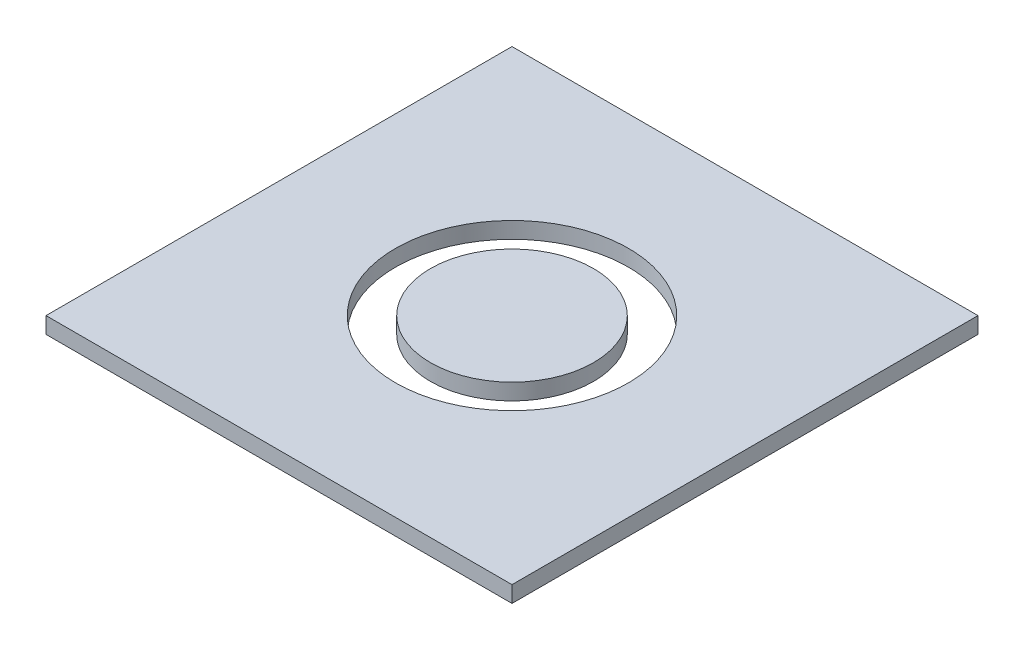
SolidWorks part; units mm, degrees
ref_plane "Front Plane" through (0, 0, 0) normal (0, 0, 1) x (1, 0, 0)
ref_plane "Top Plane" through (0, 0, 0) normal (0, 1, 0) x (1, 0, 0)
ref_plane "Right Plane" through (0, 0, 0) normal (1, 0, 0) x (0, 0, -1)
sketch "Sketch3" plane through (0, 0, 0) normal (0, 1, 0) x (1, 0, 0)
  line L1 (-10, 10) -> (10, 10)
  line L2 (-10, 10) -> (-10, -10)
  line L3 (-10, -10) -> (10, -10)
  line L4 (10, 10) -> (10, -10)
  line L5 (-10, 10) -> (10, -10) construction
  line L6 (-10, -10) -> (10, 10) construction
  point P0 (0, 0)
  dimension "D1" = 20
  dimension "D2" = 20
extrude "Boss-Extrude3" add sketch "Sketch3" along normal blind 0.7 contours L2 L3 L4 L1
sketch "Sketch5" plane through (0, 0.7, 0) normal (0, 1, 0) x (1, 0, 0)
  circle A0 centre (0, 0) radius 5
  dimension "D1" = 10
extrude "Cut-Extrude21" cut sketch "Sketch5" against normal blind 0.7 contours A0
sketch "Sketch6" plane through (0, 0, 0) normal (0, 1, 0) x (1, 0, 0)
  circle A0 centre (0, 0) radius 3.5
  dimension "D1" = 7
extrude "Boss-Extrude4" add sketch "Sketch6" along normal blind 0.7 separate body
